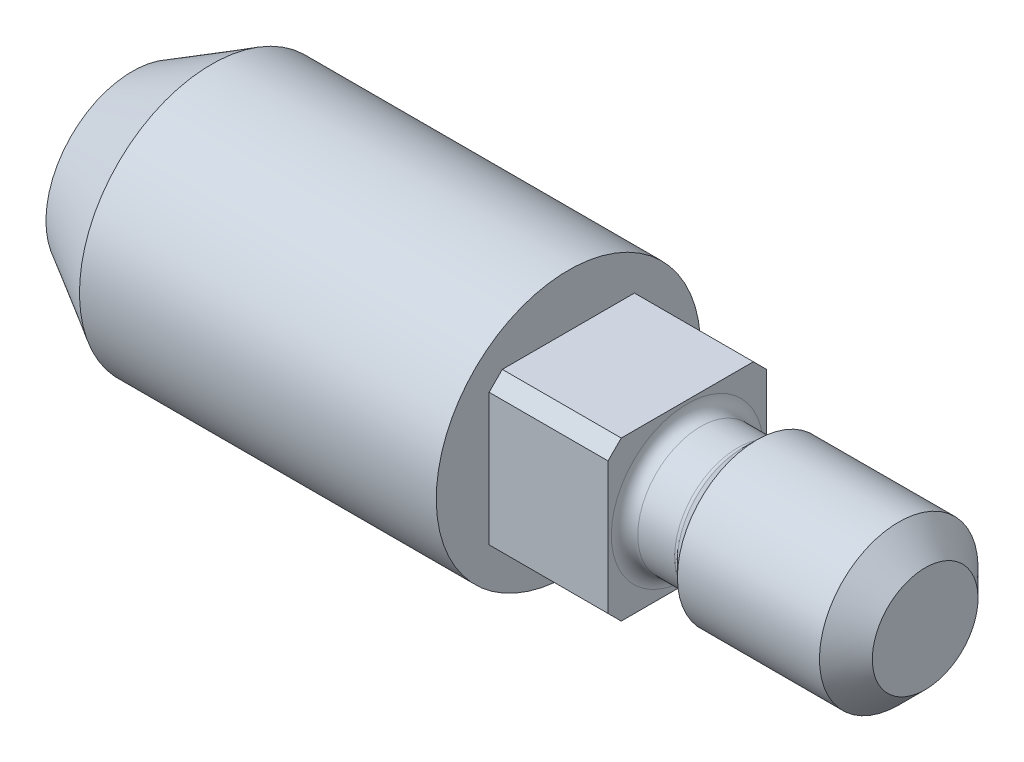
SolidWorks part; units mm, degrees
ref_plane "Спереди" through (0, 0, 0) normal (0, 0, 1) x (1, 0, 0)
ref_plane "Сверху" through (0, 0, 0) normal (0, 1, 0) x (1, 0, 0)
ref_plane "Справа" through (0, 0, 0) normal (1, 0, 0) x (0, 0, -1)
sketch "Эскиз1" plane through (0, 0, 0) normal (0, 0, 1) x (1, 0, 0)
  line L0 (0, 0) -> (136.0491, 0) construction
  line L1 (0, 6) -> (0, 6.5359)
  line L2 (0, 6.5359) -> (6, 10)
  line L3 (6, 10) -> (33, 10)
  line L4 (33, 10) -> (33, 6)
  line L5 (33, 6) -> (42, 6)
  line L6 (42, 6) -> (42, 4.75)
  line L7 (42, 4.75) -> (46, 4.75)
  line L8 (46, 4.75) -> (47.25, 6)
  line L9 (47.25, 6) -> (60, 6)
  line L10 (60, 6) -> (60, 0)
  line L11 (60, 0) -> (6, 0)
  arc A0 (6, 0) -> (0, 6) centre (0, 0) ccw
  dimension "D1" = 12
  dimension "D2" = 30
  dimension "D3" = 20
  dimension "D4" = 6
  dimension "D5" = 60
  dimension "D6" = 9
  dimension "D7" = 18
  dimension "D8" = 45
  dimension "D9" = 9.5
  dimension "D10" = 12
  dimension "D11" = 4
  dimension "D12" = 12
revolve "Повернуть1" add sketch "Эскиз1" angle 360 about L0
cosmetic thread "Условное изображение резьбы1" parameters "D2"=18.376
cosmetic thread "Условное изображение резьбы2" parameters "D2"=10.376
sketch "Эскиз2" plane through (33, 0, 0) normal (1, 0, 0) x (0, 0, -1)
  line L1 (-6, -6) -> (6, -6)
  line L2 (-6, -6) -> (-6, 6)
  line L3 (-6, 6) -> (6, 6)
  line L4 (6, -6) -> (6, 6)
  line L5 (-6, -6) -> (6, 6) construction
  line L6 (-6, 6) -> (6, -6) construction
  point P0 (0, 0)
  dimension "D1" = 12
extrude "Бобышка-Вытянуть1" add sketch "Эскиз2" along normal up to surface (9 mm away) up to face at (42, -6, 0)
chamfer "Фаска1" distance 1 angle 45 4 edges at (37.5, -6, 6) (37.5, -6, -6) (37.5, 6, -6) (37.5, 6, 6)
fillet "Скругление1" radius 1 1 edges at (42, -4.75, 0)
fillet "Скругление2" radius 0.5 1 edges at (46, -4.75, 0)
chamfer "Фаска2" distance 2 angle 45 1 edges at (60, -6, 0)
